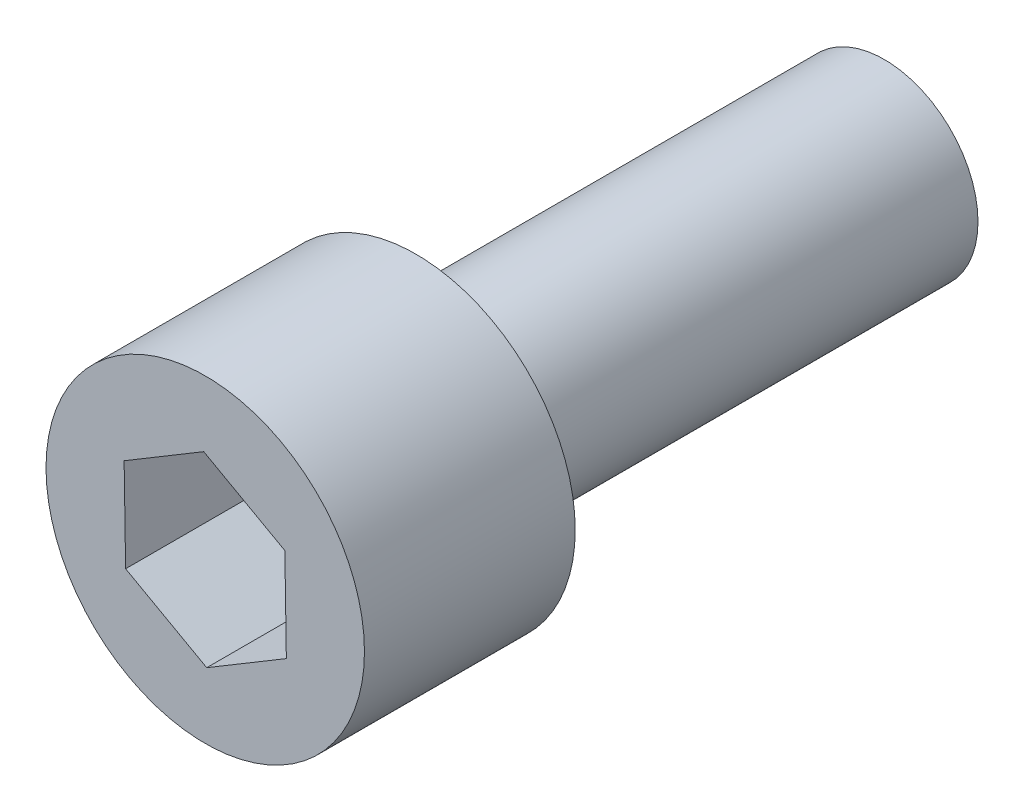
SolidWorks part; units mm, degrees
ref_plane "前视基准面" through (0, 0, 0) normal (0, 0, 1) x (1, 0, 0)
ref_plane "上视基准面" through (0, 0, 0) normal (0, 1, 0) x (1, 0, 0)
ref_plane "右视基准面" through (0, 0, 0) normal (1, 0, 0) x (0, 0, -1)
sketch "草图1" plane through (0, 0, 0) normal (0, 0, 1) x (1, 0, 0)
  circle A0 centre (0, 0) radius 2
  dimension "D1" = 4
extrude "拉伸1" add sketch "草图1" along normal blind 10
sketch "草图2" plane through (0, 0, 10) normal (0, 0, 1) x (1, 0, 0)
  line L1 (-0.0318, 1.9815) -> (-1.7319, 0.9632)
  line L2 (-1.7319, 0.9632) -> (-1.7001, -1.0183)
  line L3 (-1.7001, -1.0183) -> (0.0318, -1.9815)
  line L4 (0.0318, -1.9815) -> (1.7319, -0.9632)
  line L5 (1.7319, -0.9632) -> (1.7001, 1.0183)
  line L6 (1.7001, 1.0183) -> (-0.0318, 1.9815)
  circle A0 centre (0, 0) radius 3.4
  circle A1 centre (0, 0) radius 1.7162 construction
  dimension "D1" = 6.8
extrude "拉伸2" add sketch "草图2" along normal blind 4.5
